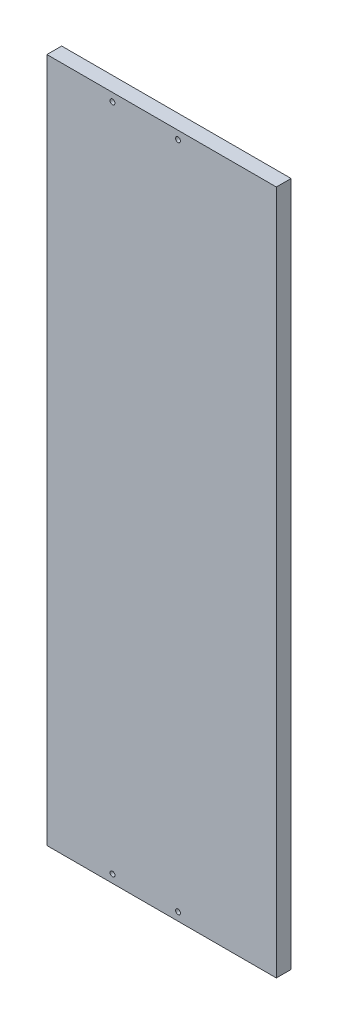
SolidWorks part; units mm, degrees
material "Береза"
ref_plane "Спереди" through (0, 0, 0) normal (0, 0, 1) x (1, 0, 0)
ref_plane "Сверху" through (0, 0, 0) normal (0, 1, 0) x (1, 0, 0)
ref_plane "Справа" through (0, 0, 0) normal (1, 0, 0) x (0, 0, -1)
ref_plane "Плоскость4" through (0, 0, 9) normal (0, 0, 1) x (1, 0, 0)
sketch "Эскиз1" plane through (0, 0, 9) normal (0, 0, 1) x (1, 0, 0)
  line L0 (140, 418) -> (0, 418)
  line L1 (0, 418) -> (0, 0)
  line L2 (0, 0) -> (140, 0)
  line L3 (140, 0) -> (140, 418)
  circle A0 centre (80, 413) radius 1.5
  circle A1 centre (40, 413) radius 1.5
  circle A2 centre (40, 5) radius 1.5
  circle A3 centre (80, 5) radius 1.5
extrude "Бобышка-Вытянуть1" add sketch "Эскиз1" against normal blind 9
